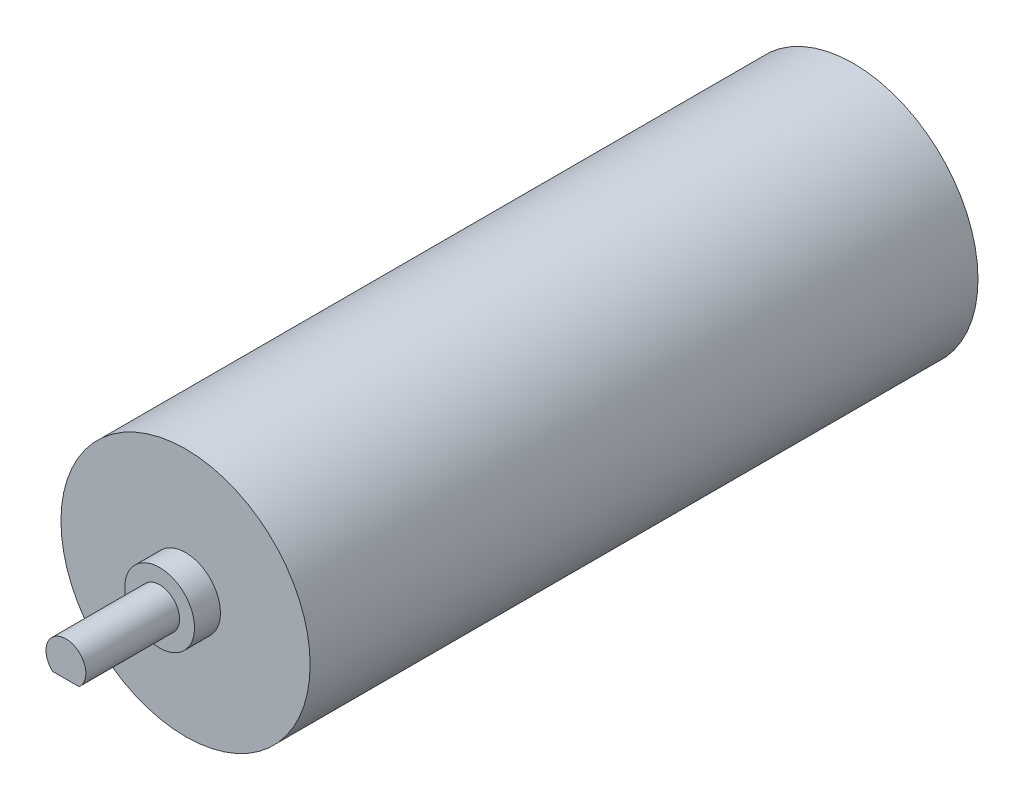
SolidWorks part; units mm, degrees
ref_plane "Front Plane" through (0, 0, 0) normal (0, 0, 1) x (1, 0, 0)
ref_plane "Top Plane" through (0, 0, 0) normal (0, 1, 0) x (1, 0, 0)
ref_plane "Right Plane" through (0, 0, 0) normal (1, 0, 0) x (0, 0, -1)
sketch "Sketch1" plane through (0, 0, 0) normal (0, 0, 1) x (1, 0, 0)
  circle A0 centre (0, 0) radius 2
extrude "Boss-Extrude1" add sketch "Sketch1" against normal blind 9.4
sketch "Sketch2" plane through (0, 0, 0) normal (0, 0, 1) x (1, 0, 0)
  line L1 (-2.641, -1.5) -> (3.359, -1.5)
  line L2 (-2.641, -1.5) -> (-2.641, -2)
  line L3 (-2.641, -2) -> (3.359, -2)
  line L4 (3.359, -1.5) -> (3.359, -2)
  circle A0 centre (0, 0) radius 2 construction
  dimension "D1" = 6
  dimension "D2" = 0.5
  dimension "D3" = 1.5
ref_plane "Plane1" through (0, 2, 0) normal (0, 1, 0) x (1, 0, 0)
extrude "Cut-Extrude1" cut sketch "Sketch2" against normal blind 8
sketch "Sketch3" plane through (0, 0, -9.4) normal (0, 0, -1) x (-1, 0, 0)
  circle A0 centre (0, 0) radius 3.5
extrude "Boss-Extrude2" add sketch "Sketch3" along normal blind 2.6 contours A0
sketch "Sketch4" plane through (0, 0, -12) normal (0, 0, -1) x (-1, 0, 0)
  circle A0 centre (0, 0) radius 12.5
extrude "Extrude-Thin1" add sketch "Sketch4" along normal blind 67 separate body thin thin type one direction reverse wall 0.1
sketch "Sketch6" plane through (0, 0, -12) normal (0, 0, -1) x (-1, 0, 0)
  circle A0 centre (0, 0) radius 12.5
extrude "Boss-Extrude4" add sketch "Sketch6" along normal blind 0.1
sketch "Sketch7" plane through (0, 0, -79) normal (0, 0, -1) x (-1, 0, 0)
  circle A0 centre (0, 0) radius 12.5
extrude "Boss-Extrude5" add sketch "Sketch7" against normal blind 0.1
